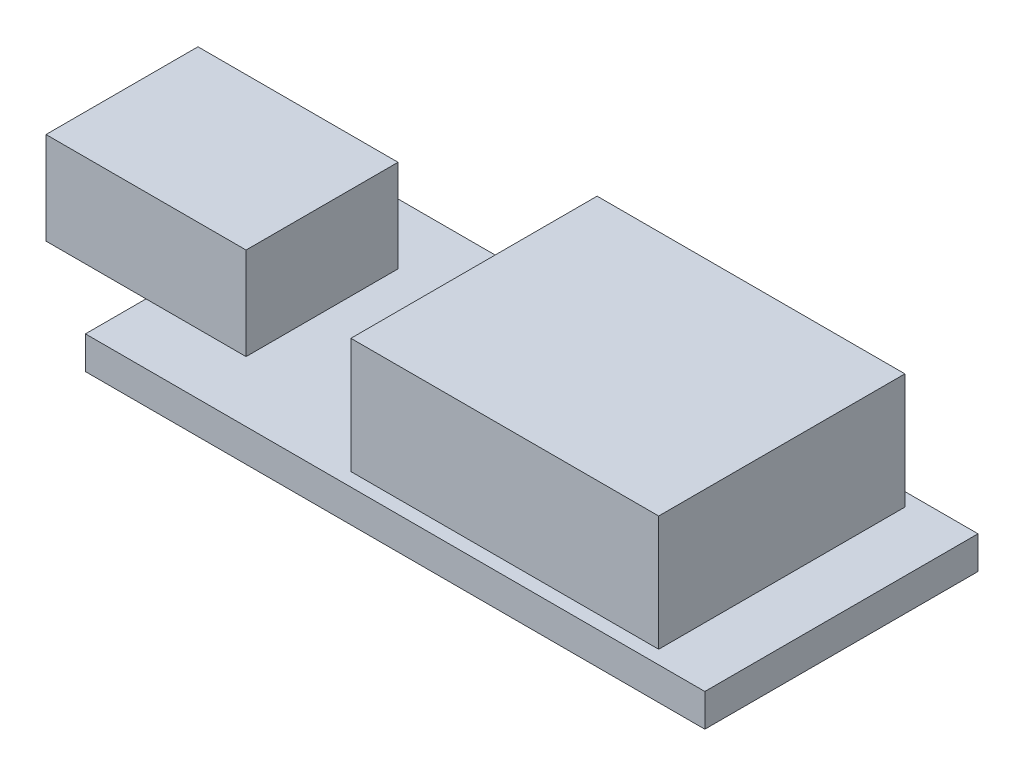
SolidWorks part; units mm, degrees
ref_plane "Front Plane" through (0, 0, 0) normal (0, 0, 1) x (1, 0, 0)
ref_plane "Top Plane" through (0, 0, 0) normal (0, 1, 0) x (1, 0, 0)
ref_plane "Right Plane" through (0, 0, 0) normal (1, 0, 0) x (0, 0, -1)
sketch "Sketch1" plane through (0, 0, 0) normal (0, 1, 0) x (1, 0, 0)
  line L1 (-16.1, 7.1) -> (16.1, 7.1)
  line L2 (-16.1, 7.1) -> (-16.1, -7.1)
  line L3 (-16.1, -7.1) -> (16.1, -7.1)
  line L4 (16.1, 7.1) -> (16.1, -7.1)
  line L5 (-16.1, 7.1) -> (16.1, -7.1) construction
  line L6 (-16.1, -7.1) -> (16.1, 7.1) construction
  circle A0 centre (-5.95, 0) radius 1.35
  point P0 (0, 0)
  point P8 (-7.9905, 0.7422)
  point P9 (0, 0)
  dimension "D3" = 2.7
  dimension "D1" = 14.2
  dimension "D2" = 32.2
  dimension "D5" = 8.8
extrude "Boss-Extrude1" add sketch "Sketch1" along normal blind 1.7
sketch "Sketch2" plane through (0, 1.7, 0) normal (0, 1, 0) x (1, 0, 0)
  line L0 (16.1, -7.1) -> (16.1, 7.1) construction
  line L1 (-3, 6.4) -> (13, 6.4)
  line L2 (-3, 6.4) -> (-3, -6.4)
  line L3 (-3, -6.4) -> (13, -6.4)
  line L4 (13, 6.4) -> (13, -6.4)
  line L5 (-3, 6.4) -> (13, -6.4) construction
  line L6 (-3, -6.4) -> (13, 6.4) construction
  point P0 (5, 0)
  point P5 (0, 0)
  dimension "D1" = 12.8
  dimension "D2" = 16
  dimension "D3" = 3.1
extrude "Boss-Extrude2" add sketch "Sketch2" along normal blind 6
sketch "Sketch3" plane through (0, 1.7, 0) normal (0, 1, 0) x (1, 0, 0)
  line L0 (-16.1, 7.1) -> (-16.1, -7.1) construction
  line L1 (-21.3, 3.95) -> (-10.9, 3.95)
  line L2 (-21.3, 3.95) -> (-21.3, -3.95)
  line L3 (-21.3, -3.95) -> (-10.9, -3.95)
  line L4 (-10.9, 3.95) -> (-10.9, -3.95)
  line L5 (-21.3, 3.95) -> (-10.9, -3.95) construction
  line L6 (-21.3, -3.95) -> (-10.9, 3.95) construction
  point P0 (-16.1, 0)
  dimension "D1" = 5.2
  dimension "D2" = 7.9
extrude "Boss-Extrude3" add sketch "Sketch3" along normal blind 4.8
